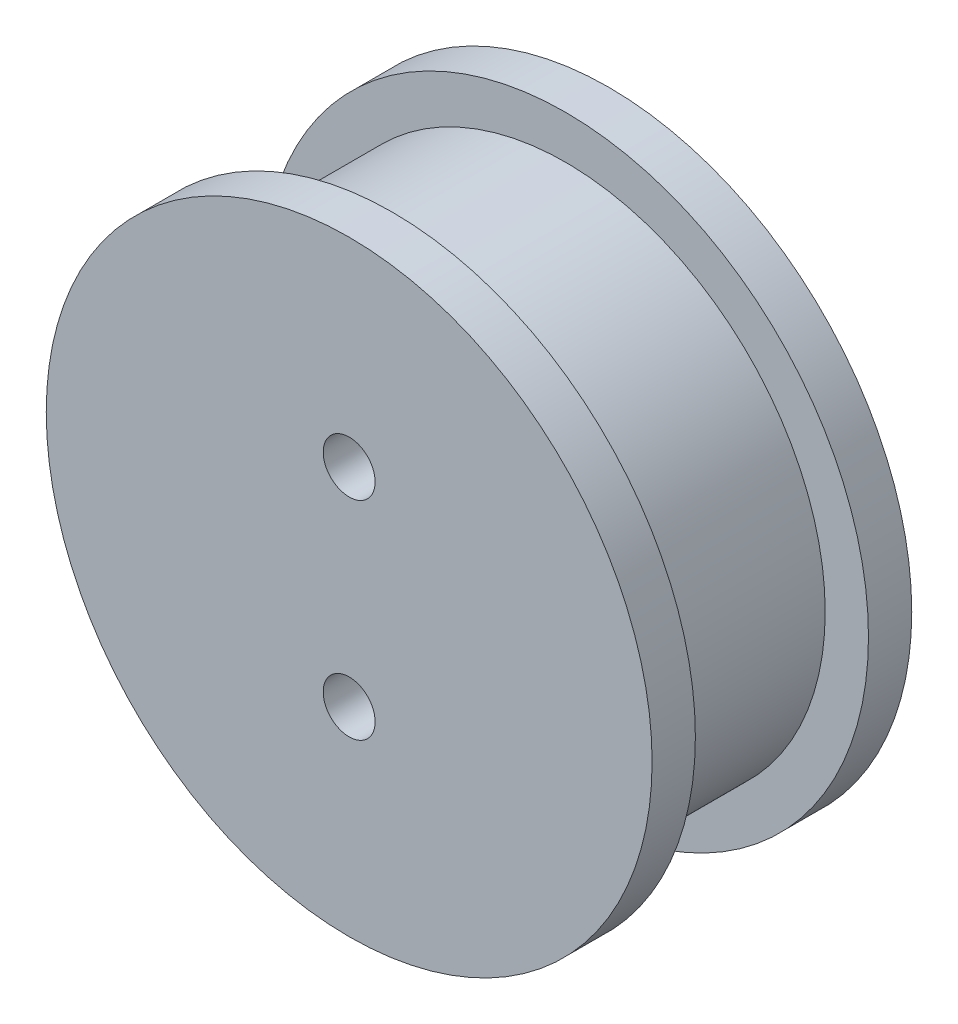
SolidWorks part; units mm, degrees
ref_plane "Alzado" through (0, 0, 0) normal (1, 0, 0) x (0, 1, 0)
ref_plane "Planta" through (0, 0, 0) normal (0, 0, 1) x (0, 1, 0)
ref_plane "Vista lateral" through (0, 0, 0) normal (0, 1, 0) x (-1, 0, 0)
sketch "Croquis1" plane through (0, 0, 0) normal (0, 0, 1) x (0, 1, 0)
  circle A0 centre (0, 0) radius 17.5
  dimension "D1" = 35
extrude "Saliente-Extruir1" add sketch "Croquis1" along normal mid plane 15
sketch "Croquis2" plane through (0, 0, 0) normal (0, 0, 1) x (0, 1, 0)
  circle A0 centre (0, 0) radius 17.5
  circle A1 centre (0, 0) radius 15
  dimension "D1" = 30
extrude "Cortar-Extruir1" cut sketch "Croquis2" against normal mid plane 10
sketch "Croquis3" plane through (0, 0, 0) normal (0, 0, 1) x (0, 1, 0)
  line L0 (0, 0) -> (0, -5.1467) construction
  circle A0 centre (6, 0) radius 1.5
  circle A1 centre (-6, 0) radius 1.5
  dimension "D1" = 3
  dimension "D2" = 6
extrude "Cortar-Extruir2" cut sketch "Croquis3" against normal mid plane 20
